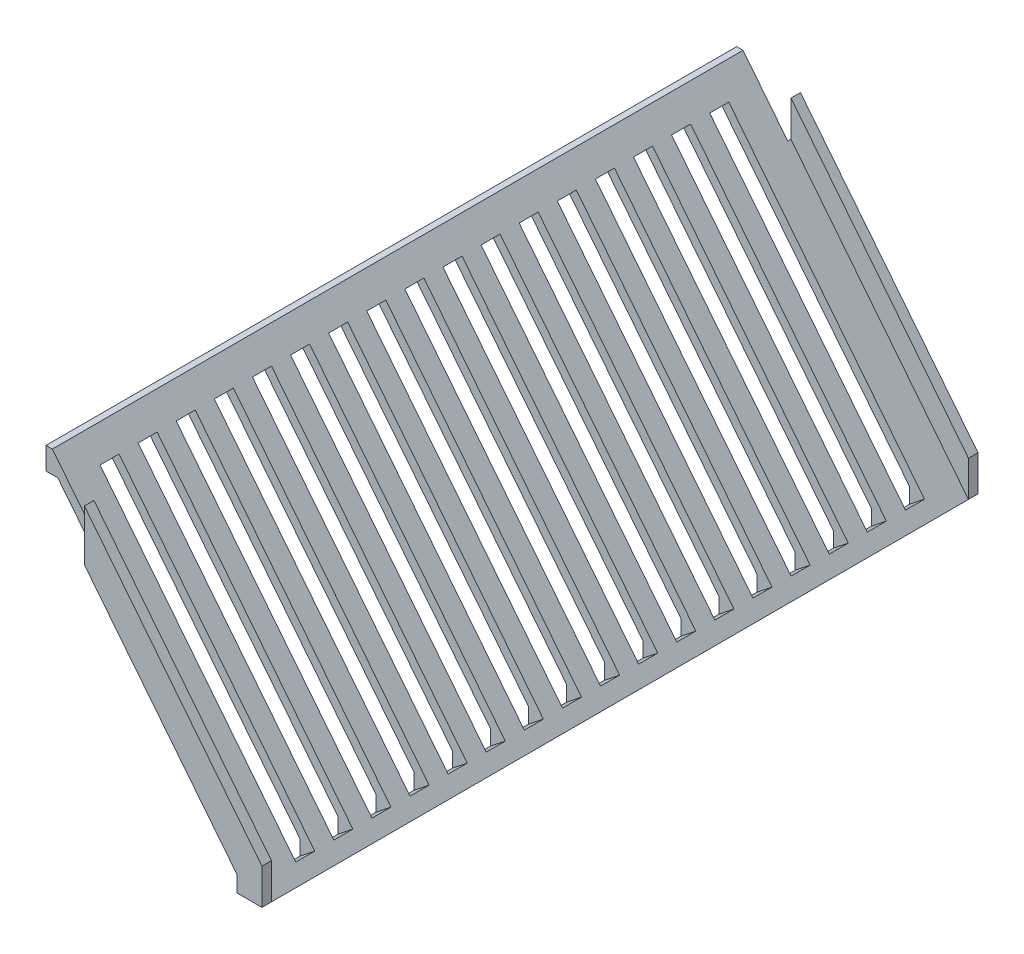
SolidWorks part; units mm, degrees
ref_plane "前视基准面" through (0, 0, 0) normal (0, 0, 1) x (1, 0, 0)
ref_plane "上视基准面" through (0, 0, 0) normal (0, 1, 0) x (1, 0, 0)
ref_plane "右视基准面" through (0, 0, 0) normal (1, 0, 0) x (0, 0, -1)
sketch "草图1" plane through (0, 0, 0) normal (0, 0, 1) x (1, 0, 0)
  line L24 (11.2841, 15.6489) -> (3.4734, 15.6489)
  line L25 (3.4734, 15.6489) -> (3.4734, 20.6489)
  line L28 (-56.9811, 96.6489) -> (-58.7159, 96.6489)
  line L35 (-56.9811, 96.6489) -> (3.4734, 20.6489)
  line L36 (-58.7159, 96.6489) -> (-58.7159, 103.6489)
  line L38 (-58.7159, 103.6489) -> (11.2841, 15.6489)
  dimension "D1" = 7
  dimension "D2" = 5
  dimension "D3" = 81
  dimension "D4" = 70
  dimension "D5" = 3
extrude "凸台-拉伸1" add sketch "草图1" along normal mid plane 224
sketch "草图4" plane through (0, 15.6489, 0) normal (0, -1, 0) x (1, 0, 0)
  line L3 (0, 0) -> (3.4734, 0) construction
  line L4 (3.4734, 112) -> (3.4734, -112) construction
  circle A0 centre (-6.2149, -115.76) radius 1.5
  dimension "D1" = 115.76
sketch "草图7" plane through (14.535, 11.562, 0) normal (0.7826, 0.6225, 0) x (0.6225, -0.7826, 0)
  line L0 (-117.6678, -112) -> (-117.6678, 112) construction
  line L1 (-117.6678, -109.5) -> (-67.6678, -109.5)
  line L2 (-117.6678, -109.5) -> (-117.6678, -101.3)
  line L3 (-117.6678, -101.3) -> (-67.6678, -101.3)
  line L4 (-67.6678, -109.5) -> (-67.6678, -101.3)
  line L5 (-117.6678, -109.5) -> (-67.6678, -101.3) construction
  line L6 (-117.6678, -101.3) -> (-67.6678, -109.5) construction
  line L7 (-5.2223, -112) -> (-117.6678, -112) construction
  line L8 (-117.6678, -75.075) -> (-117.6678, -67.075)
  line L9 (-117.6678, -88.625) -> (-67.6678, -88.625)
  line L10 (-117.6678, -88.625) -> (-117.6678, -80.625)
  line L11 (-117.6678, -80.625) -> (-67.6678, -80.625)
  line L12 (-67.6678, -88.625) -> (-67.6678, -80.625)
  line L13 (-117.6678, -88.625) -> (-67.6678, -80.625) construction
  line L14 (-117.6678, -80.625) -> (-67.6678, -88.625) construction
  line L15 (-117.6678, -75.075) -> (-67.6678, -75.075)
  line L16 (-67.6678, -75.075) -> (-67.6678, -67.075)
  line L17 (-117.6678, -67.075) -> (-67.6678, -67.075)
  line L18 (-117.6678, -61.525) -> (-117.6678, -53.525)
  line L19 (-117.6678, -61.525) -> (-67.6678, -61.525)
  line L20 (-67.6678, -61.525) -> (-67.6678, -53.525)
  line L21 (-117.6678, -53.525) -> (-67.6678, -53.525)
  line L22 (-117.6678, -47.975) -> (-117.6678, -39.975)
  line L23 (-117.6678, -47.975) -> (-67.6678, -47.975)
  line L24 (-67.6678, -47.975) -> (-67.6678, -39.975)
  line L25 (-117.6678, -39.975) -> (-67.6678, -39.975)
  line L26 (-117.6678, -34.425) -> (-117.6678, -26.425)
  line L27 (-117.6678, -34.425) -> (-67.6678, -34.425)
  line L28 (-67.6678, -34.425) -> (-67.6678, -26.425)
  line L29 (-117.6678, -26.425) -> (-67.6678, -26.425)
  line L30 (-117.6678, -20.875) -> (-117.6678, -12.875)
  line L31 (-117.6678, -20.875) -> (-67.6678, -20.875)
  line L32 (-67.6678, -20.875) -> (-67.6678, -12.875)
  line L33 (-117.6678, -12.875) -> (-67.6678, -12.875)
  line L34 (-117.6678, -7.325) -> (-117.6678, 0.675)
  line L35 (-117.6678, -7.325) -> (-67.6678, -7.325)
  line L36 (-67.6678, -7.325) -> (-67.6678, 0.675)
  line L37 (-117.6678, 0.675) -> (-67.6678, 0.675)
  line L38 (-117.6678, 6.225) -> (-117.6678, 14.225)
  line L39 (-117.6678, 6.225) -> (-67.6678, 6.225)
  line L40 (-67.6678, 6.225) -> (-67.6678, 14.225)
  line L41 (-117.6678, 14.225) -> (-67.6678, 14.225)
  line L42 (-117.6678, 19.775) -> (-117.6678, 27.775)
  line L43 (-117.6678, 19.775) -> (-67.6678, 19.775)
  line L44 (-67.6678, 19.775) -> (-67.6678, 27.775)
  line L45 (-117.6678, 27.775) -> (-67.6678, 27.775)
  line L46 (-117.6678, 33.325) -> (-117.6678, 41.325)
  line L47 (-117.6678, 33.325) -> (-67.6678, 33.325)
  line L48 (-67.6678, 33.325) -> (-67.6678, 41.325)
  line L49 (-117.6678, 41.325) -> (-67.6678, 41.325)
  line L50 (-117.6678, 46.875) -> (-117.6678, 54.875)
  line L51 (-117.6678, 46.875) -> (-67.6678, 46.875)
  line L52 (-67.6678, 46.875) -> (-67.6678, 54.875)
  line L53 (-117.6678, 54.875) -> (-67.6678, 54.875)
  line L54 (-117.6678, 60.425) -> (-117.6678, 68.425)
  line L55 (-117.6678, 60.425) -> (-67.6678, 60.425)
  line L56 (-67.6678, 60.425) -> (-67.6678, 68.425)
  line L57 (-117.6678, 68.425) -> (-67.6678, 68.425)
  line L58 (40.7429, 0) -> (-56.4992, 0) construction
  line L59 (-117.6678, 109.5) -> (-67.6678, 109.5)
  line L60 (-67.6678, 109.5) -> (-67.6678, 101.3)
  line L61 (-117.6678, 101.3) -> (-67.6678, 101.3)
  line L62 (-117.6678, 109.5) -> (-117.6678, 101.3)
  point P4 (-92.6678, -105.4)
  point P13 (-92.6678, -84.625)
  dimension "D1" = 2.5
  dimension "D2" = 50
  dimension "D3" = 8.2
  dimension "D4" = 50
  dimension "D5" = 8
  dimension "D6" = 12.675
  dimension "D7" = 12
ref_plane "基准面5" through (-52.2629, 101.4336, 91.9) normal (0, 0, 1) x (1, 0, 0)
sketch "草图8" plane through (0, 0, -112) normal (0, 0, -1) x (-1, 0, 0)
  line L0 (-3.4734, 15.6489) -> (-11.2841, 15.6489)
  line L1 (-11.2841, 15.6489) -> (-11.2841, 26.8935)
  line L2 (-11.2841, 26.8935) -> (49.7714, 103.6489)
  line L4 (58.7159, 103.6489) -> (58.7159, 96.6489)
  line L5 (58.7159, 96.6489) -> (56.9811, 96.6489)
  line L6 (56.9811, 96.6489) -> (-3.4734, 20.6489)
  line L7 (-3.4734, 20.6489) -> (-3.4734, 15.6489)
  line L9 (58.7159, 103.6489) -> (49.7714, 103.6489)
  dimension "D1" = 10
extrude "凸台-拉伸2" add sketch "草图8" along normal blind 0.75 and the other way blind 2.25
mirror "镜向1" about plane through (0, 0, 0) normal (0, 0, 1) of "凸台-拉伸2"
sketch "草图9" plane through (14.535, 11.562, 0) normal (0.7826, 0.6225, 0) x (0, 0, -1)
  line L0 (0, 5.2223) -> (0, 117.6678) construction
  line L1 (-109.75, 5.2223) -> (109.75, 5.2223) construction
  line L2 (-109.75, 117.6678) -> (109.75, 117.6678) construction
  line L3 (9, 10.2223) -> (9, 109.2223)
  line L4 (-3, 10.2223) -> (3, 10.2223)
  line L5 (-3, 10.2223) -> (-3, 109.2223)
  line L6 (-3, 109.2223) -> (3, 109.2223)
  line L7 (3, 10.2223) -> (3, 109.2223)
  line L8 (0, 109.2223) -> (0, 10.2223) construction
  line L9 (-3, 59.7223) -> (3, 59.7223) construction
  line L10 (15, 10.2223) -> (15, 109.2223)
  line L11 (9, 109.2223) -> (15, 109.2223)
  line L12 (9, 10.2223) -> (15, 10.2223)
  line L13 (21, 10.2223) -> (21, 109.2223)
  line L14 (27, 10.2223) -> (27, 109.2223)
  line L15 (21, 109.2223) -> (27, 109.2223)
  line L16 (21, 10.2223) -> (27, 10.2223)
  line L17 (33, 10.2223) -> (33, 109.2223)
  line L18 (39, 10.2223) -> (39, 109.2223)
  line L19 (33, 109.2223) -> (39, 109.2223)
  line L20 (33, 10.2223) -> (39, 10.2223)
  line L21 (45, 10.2223) -> (45, 109.2223)
  line L22 (51, 10.2223) -> (51, 109.2223)
  line L23 (45, 109.2223) -> (51, 109.2223)
  line L24 (45, 10.2223) -> (51, 10.2223)
  line L25 (57, 10.2223) -> (57, 109.2223)
  line L26 (63, 10.2223) -> (63, 109.2223)
  line L27 (57, 109.2223) -> (63, 109.2223)
  line L28 (57, 10.2223) -> (63, 10.2223)
  line L29 (69, 10.2223) -> (69, 109.2223)
  line L30 (75, 10.2223) -> (75, 109.2223)
  line L31 (69, 109.2223) -> (75, 109.2223)
  line L32 (69, 10.2223) -> (75, 10.2223)
  line L33 (81, 10.2223) -> (81, 109.2223)
  line L34 (87, 10.2223) -> (87, 109.2223)
  line L35 (81, 109.2223) -> (87, 109.2223)
  line L36 (81, 10.2223) -> (87, 10.2223)
  line L37 (93, 10.2223) -> (93, 109.2223)
  line L38 (99, 10.2223) -> (99, 109.2223)
  line L39 (93, 109.2223) -> (99, 109.2223)
  line L40 (93, 10.2223) -> (99, 10.2223)
  line L41 (-15, 10.2223) -> (-15, 109.2223)
  line L42 (-9, 10.2223) -> (-9, 109.2223)
  line L43 (-15, 109.2223) -> (-9, 109.2223)
  line L44 (-15, 10.2223) -> (-9, 10.2223)
  line L45 (-27, 10.2223) -> (-27, 109.2223)
  line L46 (-21, 10.2223) -> (-21, 109.2223)
  line L47 (-27, 109.2223) -> (-21, 109.2223)
  line L48 (-27, 10.2223) -> (-21, 10.2223)
  line L49 (-39, 10.2223) -> (-39, 109.2223)
  line L50 (-33, 10.2223) -> (-33, 109.2223)
  line L51 (-39, 109.2223) -> (-33, 109.2223)
  line L52 (-39, 10.2223) -> (-33, 10.2223)
  line L53 (-51, 10.2223) -> (-51, 109.2223)
  line L54 (-45, 10.2223) -> (-45, 109.2223)
  line L55 (-51, 109.2223) -> (-45, 109.2223)
  line L56 (-51, 10.2223) -> (-45, 10.2223)
  line L57 (-63, 10.2223) -> (-63, 109.2223)
  line L58 (-57, 10.2223) -> (-57, 109.2223)
  line L59 (-63, 109.2223) -> (-57, 109.2223)
  line L60 (-63, 10.2223) -> (-57, 10.2223)
  line L61 (-75, 10.2223) -> (-75, 109.2223)
  line L62 (-69, 10.2223) -> (-69, 109.2223)
  line L63 (-75, 109.2223) -> (-69, 109.2223)
  line L64 (-75, 10.2223) -> (-69, 10.2223)
  line L65 (-87, 10.2223) -> (-87, 109.2223)
  line L66 (-81, 10.2223) -> (-81, 109.2223)
  line L67 (-87, 109.2223) -> (-81, 109.2223)
  line L68 (-87, 10.2223) -> (-81, 10.2223)
  line L69 (-99, 10.2223) -> (-99, 109.2223)
  line L70 (-93, 10.2223) -> (-93, 109.2223)
  line L71 (-99, 109.2223) -> (-93, 109.2223)
  line L72 (-99, 10.2223) -> (-93, 10.2223)
  dimension "D1" = 6
  dimension "D2" = 99
  dimension "D5" = 5
  dimension "D3" = 9
  dimension "D4" = 9
extrude "切除-拉伸3" cut sketch "草图9" against normal blind 10
ref_plane "基准面4" through (0, 0, 115.75) normal (0, 0, 1) x (1, 0, 0)
sketch "草图10" plane through (-58.7159, 0, 0) normal (-1, 0, 0) x (0, 0, 1)
  line L1 (112.75, 103.6489) -> (-112.75, 103.6489)
  line L2 (112.75, 103.6489) -> (112.75, 96.6489)
  line L3 (112.75, 96.6489) -> (-112.75, 96.6489)
  line L4 (-112.75, 103.6489) -> (-112.75, 96.6489)
  line L5 (112.75, 103.6489) -> (-112.75, 96.6489) construction
  line L6 (112.75, 96.6489) -> (-112.75, 103.6489) construction
  point P4 (0, 100.1489)
extrude "凸台-拉伸3" add sketch "草图10" along normal blind 2
sketch "草图5" plane through (0, 96.6489, 0) normal (0, -1, 0) x (1, 0, 0)
  line L2 (-60.7159, -112.75) -> (-60.7159, 112.75) construction
  circle A0 centre (-58.7159, -86.5) radius 1.5
  circle A1 centre (-58.7159, 86.5) radius 1.5
  dimension "D1" = 2
  dimension "D2" = 173
extrude "切除-拉伸2" cut sketch "草图5" against normal blind 2
sketch "草图12" plane through (0, 0, 112.75) normal (0, 0, 1) x (1, 0, 0)
  line L0 (-60.7159, 103.6489) -> (-60.7159, 96.598)
  line L1 (-60.7159, 103.6489) -> (-49.7714, 103.6489) construction
  line L2 (-60.7159, 96.6489) -> (-60.7159, 103.6489) construction
  line L5 (-49.7714, 103.6489) -> (11.2841, 26.8935) construction
  line L6 (-49.7714, 103.6489) -> (-60.7159, 103.6489)
  line L7 (-49.7714, 103.6489) -> (-44.6242, 97.1782)
  line L8 (-44.6242, 97.1782) -> (-44.6242, 81.1145)
  line L9 (3.4734, 20.6489) -> (-56.9811, 96.6489) construction
  line L10 (-44.6242, 81.1145) -> (-56.9811, 96.6489)
  line L11 (-56.9811, 96.6489) -> (-60.7159, 96.598)
extrude "切除-拉伸4" cut sketch "草图12" against normal blind 4
mirror "镜向2" about plane through (0, 0, 0) normal (0, 0, 1) of "切除-拉伸4"
